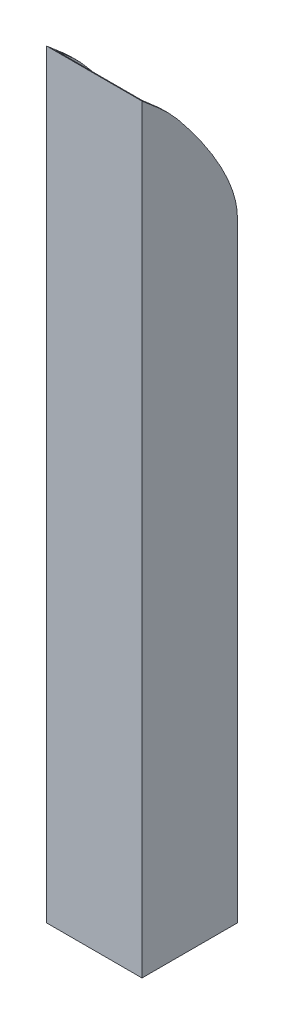
SolidWorks part; units mm, degrees
ref_plane "Front Plane" through (0, 0, 0) normal (0, 0, 1) x (1, 0, 0)
ref_plane "Top Plane" through (0, 0, 0) normal (0, 1, 0) x (1, 0, 0)
ref_plane "Right Plane" through (0, 0, 0) normal (1, 0, 0) x (0, 0, -1)
sketch "Sketch2" plane through (0, 0, 0) normal (0, 1, 0) x (1, 0, 0)
  line L0 (-11.4554, 11.4554) -> (11.4554, 11.4554)
  line L1 (-12.7, -12.7) -> (12.7, -12.7)
  line L2 (-12.7, -12.7) -> (-12.7, 12.7)
  line L3 (-12.7, 12.7) -> (12.7, 12.7)
  line L4 (12.7, -12.7) -> (12.7, 12.7)
  line L5 (-12.7, -12.7) -> (12.7, 12.7) construction
  line L6 (-12.7, 12.7) -> (12.7, -12.7) construction
  line L7 (11.4554, -11.4554) -> (11.4554, 11.4554)
  line L8 (-11.4554, -11.4554) -> (11.4554, -11.4554)
  line L9 (-11.4554, -11.4554) -> (-11.4554, 11.4554)
  point P0 (0, 0)
  dimension "D1" = 25.4
  dimension "D2" = 1.2446
extrude "Boss-Extrude1" add sketch "Sketch2" along normal blind 254
sketch "Sketch3" plane through (12.7, 0, 0) normal (1, 0, 0) x (0, 0, -1)
  line L0 (12.7, 254) -> (12.7, 0) construction
  line L1 (-12.7, 0) -> (12.7, 0) construction
  line L2 (12.7, 181.5092) -> (12.7, 143.5744) construction
  line L3 (-12.7, 254) -> (-12.7, 0) construction
  line L4 (-68.2764, 258.0688) -> (34.4761, 258.0688)
  line L5 (34.4761, 258.0688) -> (34.4761, 162.56)
  line L6 (34.4761, 162.56) -> (12.7, 162.56)
  spline S0 degree 3 poles (12.7, 162.56) (12.7, 171.2631) (-14.037, 210.4399) (-6.8192, 191.7249) (-68.2764, 258.0688) knots 0 0 0 0 0.291428 1 1 1 1
  point P10 (-12.7, 202.184)
  dimension "D1" = 162.56
  dimension "D2" = 47.0661
  dimension "D3" = 39.624
extrude "Cut-Extrude1" cut sketch "Sketch3" against normal through all
sketch "Sketch4" plane through (0, 0, 0) normal (1, 0, 0) x (0, 0, -1)
  line L0 (12.7, 162.56) -> (12.7, 127)
  line L1 (-12.7, 202.184) -> (-25.7434, 213.36)
  spline S0 degree 3 poles (-2556.1451, 3288.8408) (106.5221, -22.3697) (-170.6717, 478.6809) (221.001, -160.6628) (-3454.7674, 2147.7378) knots -1.626775 -1.626775 -1.626775 -1.626775 0.708572 2.811553 2.811553 2.811553 2.811553 only from (-12.7, 202.184) to (12.7, 162.56) construction
  spline S1 degree 3 poles (-12.7, 202.184) (-7.1378, 197.4182) (-3.2945, 194.6993) (12.7, 171.2631) (12.7, 162.56) knots 0.401783 0.401783 0.401783 0.401783 0.708572 1 1 1 1
  dimension "D1" = 35.56
  dimension "D2" = 50.8
